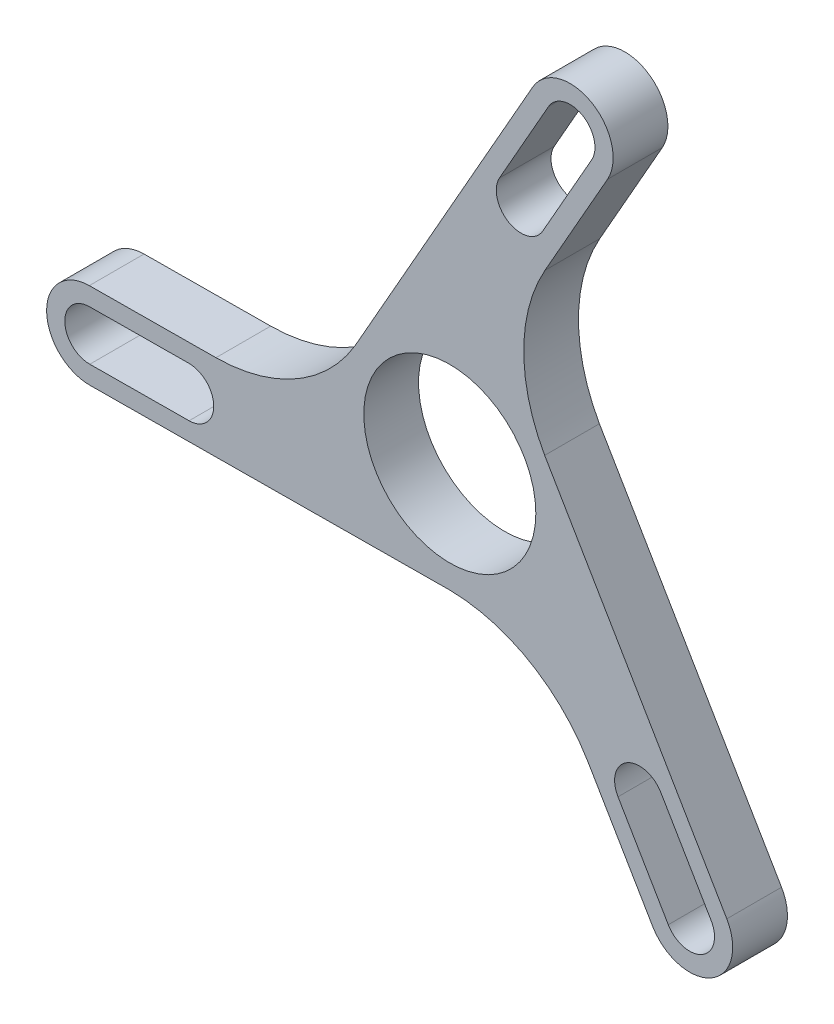
SolidWorks part; units mm, degrees
ref_plane "Front Plane" through (0, 0, 0) normal (0, 0, 1) x (1, 0, 0)
ref_plane "Top Plane" through (0, 0, 0) normal (0, 1, 0) x (1, 0, 0)
ref_plane "Right Plane" through (0, 0, 0) normal (1, 0, 0) x (0, 0, -1)
sketch "Sketch1" plane through (0, 0, 0) normal (0, 0, 1) x (1, 0, 0)
  line L0 (10.6044, 47.0212) -> (-12.1737, 6.9138)
  line L1 (12.1716, 27.5064) -> (20.1695, 41.589)
  line L2 (15.3869, 44.3051) -> (10.6831, 36.0226) construction
  line L3 (12.6261, 45.8731) -> (6.3543, 34.8298)
  line L4 (11.876, 31.6939) -> (18.1478, 42.7372)
  line L5 (7.5472, 30.501) -> (-1.8975, 13.8708) construction
  line L6 (35.4194, -32.6943) -> (12.0744, 7.0859)
  line L7 (17.7355, -24.2941) -> (25.9324, -38.2618)
  line L8 (33.4142, -33.8711) -> (26.9863, -22.9179)
  line L9 (21.5097, -26.1318) -> (27.9376, -37.085)
  line L10 (30.6759, -35.478) -> (25.855, -27.2631) construction
  line L11 (22.641, -21.7865) -> (12.9612, -5.2921) construction
  line L12 (-46.0238, -14.3269) -> (0.0993, -13.9996)
  line L13 (-29.907, -3.2123) -> (-46.1018, -3.3272)
  line L14 (-46.0403, -12.002) -> (-33.3406, -11.9119)
  line L15 (-33.3857, -5.562) -> (-46.0854, -5.6522)
  line L16 (-46.0628, -8.8271) -> (-36.5381, -8.7595) construction
  line L17 (-30.1882, -8.7144) -> (-11.0637, -8.5787) construction
  circle A0 centre (0, 0) radius 11
  circle A1 centre (0, 0) radius 14
  arc A2 (18.1478, 42.7372) -> (12.6261, 45.8731) centre (15.3869, 44.3051) ccw
  arc A3 (20.1695, 41.589) -> (10.6044, 47.0212) centre (15.3869, 44.3051) ccw
  arc A4 (27.9376, -37.085) -> (33.4142, -33.8711) centre (30.6759, -35.478) ccw
  arc A5 (6.3543, 34.8298) -> (11.876, 31.6939) centre (9.1151, 33.2618) ccw
  arc A6 (25.9324, -38.2618) -> (35.4194, -32.6943) centre (30.6759, -35.478) ccw
  arc A7 (12.1716, 27.5064) -> (12.1729, 6.9153) centre (30.2979, 17.212) ccw
  arc A8 (26.9863, -22.9179) -> (21.5097, -26.1318) centre (24.248, -24.5248) ccw
  arc A9 (17.7355, -24.2941) -> (-0.0976, -13.9997) centre (-0.2429, -34.8448) ccw
  arc A10 (-46.0854, -5.6522) -> (-46.0403, -12.002) centre (-46.0628, -8.8271) ccw
  arc A11 (-46.1018, -3.3272) -> (-46.0238, -14.3269) centre (-46.0628, -8.8271) ccw
  arc A12 (-33.3406, -11.9119) -> (-33.3857, -5.562) centre (-33.3631, -8.737) ccw
  arc A13 (-29.907, -3.2123) -> (-12.0753, 7.0844) centre (-30.055, 17.6328) ccw
  point P52 (0, 0)
  dimension "D1" = 22
  dimension "D2" = 28
  dimension "D3" = 6.35
  dimension "D4" = 11
  dimension "D5" = 3
  dimension "D6" = 6.35
  dimension "D8" = 35
extrude "Boss-Extrude2" add sketch "Sketch1" along normal blind 7 contours L0 A13 A1 L6 A7 L1 A3 A5 L3 A2 L4 | A13 L13 A11 L12 A9 A1 L0 A12 L14 A10 L15 | A9 L7 A6 L6 A7 A1 L12 A8 L8 A4 L9 | A1 A0
